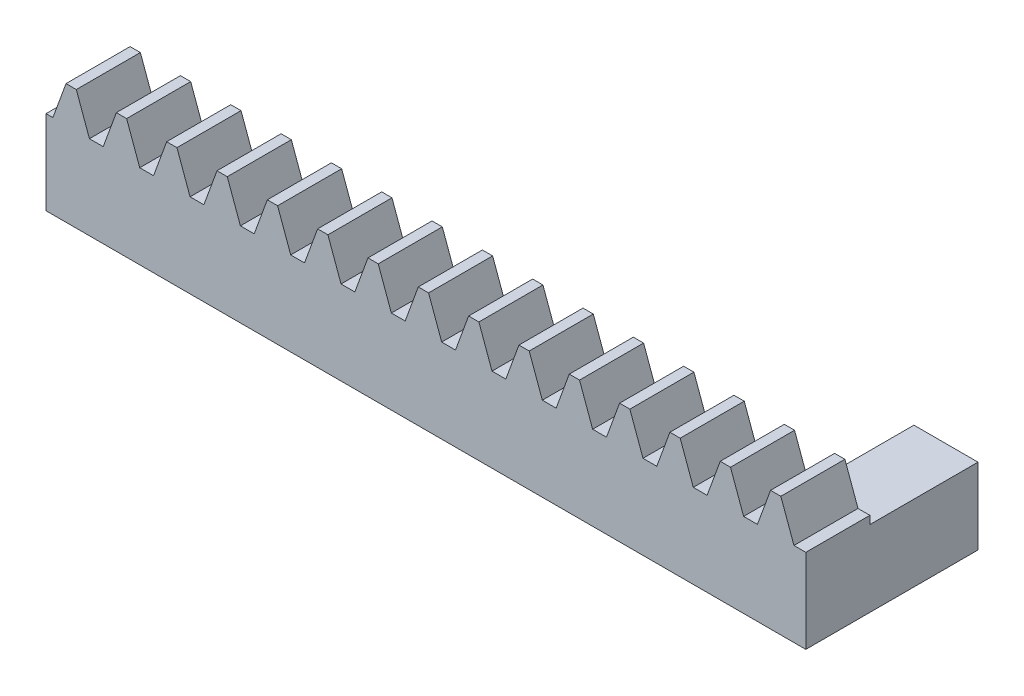
SolidWorks part; units mm, degrees
extrude "Blank" add sketch "BlankSke" against normal blind 8
sketch "BlankSke" plane through (0, 0, 0) normal (0, 0, 1) x (1, 0, 0)
  line L1 (0, 0) -> (120, 0)
  line L2 (0, 0) -> (0, 16)
  line L3 (0, 16) -> (120, 16)
  line L4 (120, 0) -> (120, 16)
  dimension "Length" = 120
  dimension "Blank_height" = 16
ref_plane "Plane1" through (0, 0, 0) normal (0, 0, 1) x (1, 0, 0)
ref_plane "Plane2" through (0, 0, 0) normal (0, 1, 0) x (1, 0, 0)
ref_plane "Plane3" through (0, 0, 0) normal (1, 0, 0) x (0, 0, -1)
sketch "HoldingSke" plane through (0, 0, 0) normal (0, 1, 0) x (1, 0, 0)
  line L0 (0, 0) -> (0.0696, 0.4951)
  line L1 (-15, 0) -> (100, 0) construction
  line L2 (0, 0) -> (-2.1039, 2.3779)
  line L3 (0, 0) -> (-11.863, 4.5341)
  line L4 (0, 0) -> (8.0624, 3.0949)
  line L5 (0, 0) -> (-23.7986, -8.8762)
  line L6 (0, 0) -> (-10.5278, -7.1032)
  line L9 (-71.009, 38.7566) -> (41.7541, 79.799)
  line L10 (-76.2, 4.3779) -> (-62.2, 4.3779)
  line L11 (0, 0) -> (-8, 0)
  line L12 (-76.2, 101.6) -> (-76.133, 101.6)
  line L13 (24.9733, 27.94) -> (52.9518, 28.4284)
  line L14 (24.9733, 27.94) -> (24.9743, 27.94)
  line L15 (24.9733, 27.94) -> (100.4006, 29.5858)
  circle A0 centre (0, 0) radius 19.05
  circle A1 centre (0, 0) radius 7
  circle A2 centre (0, 0) radius 12.7
  dimension "MPH" = 14
  dimension "Diameter" = 38.1
  dimension "Num_teeth" = 21
  dimension "Pitch" = 0.5
  dimension "Show_teeth" = 998
  dimension "Thickness" = 12.7
  dimension "Ap" = 20
  dimension "Pitch_height" = 14
  dimension "Width" = 8
  dimension "Backlash" = 0.067
  dimension "Addendum_fac" = 1
  dimension "Dedendum_fac" = 1.25
  dimension "Clearance_fac" = 0.25
  dimension "Dedendum_add" = 0.001
  dimension "Length" = 120
  dimension "Module" = 2
sketch "TooCutSkeIll" plane through (0, 0, 0) normal (0, 0, 1) x (1, 0, 0)
  line L0 (-2.4806, 15.9474) -> (-0.9819, 11.8296)
  line L1 (-0.5111, 11.5) -> (0.5111, 11.5)
  line L2 (0.9819, 11.8296) -> (2.4806, 15.9474)
  line L3 (120, 16) -> (0, 16) construction
  line L4 (0, 0) -> (0, 64.897) construction
  line L5 (-13.208, 14) -> (12.954, 14) construction
  line L6 (0, 0) -> (120, 0) construction
  line L7 (1.7718, 14) -> (1.7718, 48.7463) construction
  line L8 (-1.7718, 14) -> (-1.7718, 48.7463) construction
  line L9 (2.5558, 16) -> (2.5558, 16.0254)
  line L10 (-2.5558, 16) -> (-2.5558, 16.0254)
  line L11 (-2.5558, 16.0254) -> (2.5558, 16.0254)
  arc A0 (0.5111, 11.5) -> (0.9819, 11.8296) centre (0.5111, 12.001) ccw
  arc A1 (-0.9819, 11.8296) -> (-0.5111, 11.5) centre (-0.5111, 12.001) ccw
  arc A2 (2.5558, 16) -> (2.4806, 15.9474) centre (2.5558, 15.92) ccw
  arc A3 (-2.4806, 15.9474) -> (-2.5558, 16) centre (-2.5558, 15.92) ccw
  dimension "Pitch_height" = 14
  dimension "Addendum_plus" = 2.0254
  dimension "Pressure_angle" = 20
  dimension "Gap_width" = 3.5436
  dimension "Dedendum" = 2.5
extrude "ToothCutIll" [suppressed] cut sketch "TooCutSkeIll" against normal through all
sketch "TooCutSkeSim" plane through (0, 0, 0) normal (0, 0, 1) x (1, 0, 0)
  line L0 (0.8619, 11.5) -> (-0.8619, 11.5)
  line L1 (2.509, 16.0254) -> (0.8619, 11.5)
  line L2 (0, 17.4625) -> (0, 53.467) construction
  line L3 (2.509, 16.0254) -> (-2.509, 16.0254)
  line L6 (-2.509, 16.0254) -> (-0.8619, 11.5)
  line L9 (-1.7718, 14) -> (1.7718, 14) construction
  line L10 (0, 0) -> (120, 0) construction
  line L11 (1.7718, 14) -> (1.7718, 53.467) construction
  line L12 (-1.7718, 14) -> (-1.7718, 53.467) construction
  dimension "Pitch_height" = 14
  dimension "Addendum_plus" = 2.0254
  dimension "Pressure_angle" = 20
  dimension "Gap_width" = 3.5436
  dimension "Dedendum" = 2.5
extrude "ToothCutSim" cut sketch "TooCutSkeSim" against normal through all
pattern_linear "TeethCuts" count 20 spacing 6.2832 along (1, 0, 0) of "ToothCutIll", "ToothCutSim"
sketch "Sketch1" plane through (120, 0, 0) normal (1, 0, 0) x (0, 0, -1)
  line L0 (0, 1) -> (8, 1)
  line L1 (0, 0) -> (0, 11.5) construction
  line L2 (8, 0) -> (8, 11.5) construction
  line L3 (8, 1) -> (8, 0)
  line L4 (8, 0) -> (0, 0)
  line L5 (0, 0) -> (0, 1)
  dimension "D1" = 1
extrude "Cut-Extrude1" cut sketch "Sketch1" against normal through all
sketch "Sketch2" plane through (120, 0, 0) normal (1, 0, 0) x (0, 0, -1)
  line L0 (8, 1) -> (21.5, 1)
  line L6 (21.5, 10.5) -> (8, 10.5)
  line L7 (8, 1) -> (8, 11.5) construction
  line L8 (8, 10.5) -> (8, 1)
  line L14 (21.5, 10.5) -> (21.5, 1)
  dimension "D1" = 9.5
  dimension "D6" = 13.5
extrude "Boss-Extrude2" add sketch "Sketch2" against normal blind 8
sketch "Sketch3" plane through (0, 0, 0) normal (0, 0, 1) x (1, 0, 0)
  line L0 (0, 1) -> (0, 11.5)
  line L1 (0, 11.5) -> (0, 1) construction
  line L2 (0.8619, 11.5) -> (2.4997, 16)
  line L3 (2.4997, 16) -> (3.7834, 16)
  line L4 (3.7834, 16) -> (5.4213, 11.5)
  line L6 (5.4213, 11.5) -> (7.1451, 11.5) construction
  line L8 (0, 1) -> (120, 1) construction
  line L9 (6.1613, 1) -> (0, 1)
  line L10 (5.4213, 11.5) -> (7.1451, 11.5)
  line L11 (7.1451, 11.5) -> (8.7829, 16)
  line L12 (8.7829, 16) -> (10.0666, 16)
  line L13 (10.0666, 16) -> (11.7045, 11.5)
  line L14 (11.7045, 11.5) -> (13.4282, 11.5)
  line L15 (13.4282, 11.5) -> (15.0661, 16)
  line L16 (15.0661, 16) -> (15.708, 16)
  line L17 (16.3498, 16) -> (15.0661, 16) construction
  line L19 (0, 1) -> (112, 1) construction
  line L20 (15.708, 1) -> (6.1613, 1)
  line L21 (15.708, 16) -> (16.3498, 16)
  line L22 (16.3498, 16) -> (17.9877, 11.5)
  line L23 (17.9877, 11.5) -> (19.7114, 11.5)
  line L25 (19.7114, 11.5) -> (21.3493, 16)
  line L26 (17.9877, 1) -> (15.708, 1)
  line L27 (21.3493, 16) -> (22.633, 16)
  line L28 (22.633, 16) -> (24.2709, 11.5)
  line L29 (24.2709, 11.5) -> (25.1327, 11.5)
  line L40 (25.1327, 1) -> (17.9877, 1)
  line L49 (25.1327, 11.5) -> (25.1327, 1)
  arc A0 (0, 11.5) -> (0.8619, 11.5) centre (0.4309, 11.5) cw
extrude "Cut-Extrude2" cut sketch "Sketch3" against normal through all
equation "' \"Module@HoldingSke\" = 6.35"
equation "' \"Num_teeth@HoldingSke\" = 12"
equation "' \"Ap@HoldingSke\" =  20"
equation "' \"Ap@HoldingSke\" = 20"
equation "' \"Width@HoldingSke\" = 0.25 * 25.4"
equation "' \"Show_teeth@HoldingSke\" = 500"
equation "' \"Backlash@HoldingSke\" = 0.009 * 25.4"
equation "' \"Addendum_fac@HoldingSke\" = 1.0"
equation "' \"Dedendum_fac@HoldingSke\" = 1.25"
equation "' \"Dedendum_add@HoldingSke\" = 0.00005 * 25.4"
equation "' \"Clearance_fac@HoldingSke\" = 0.25"
equation "' \"Pitch_height@HoldingSke\" = 1 * 25.4"
equation "' \"Length@HoldingSke\" = 4.71 * 25.4"
equation "\"Pitch@HoldingSke\" = 1 / \"Module@HoldingSke\""
equation "\"MPH@HoldingSke\" = \"Dedendum_fac@HoldingSke\" / \"Pitch@HoldingSke\" + 2 * \"Dedendum_add@HoldingSke\" + 0.002 * 25.4"
equation "\"MPH@HoldingSke\" = ((sgn( \"MPH@HoldingSke\" - \"Pitch_height@HoldingSke\")+1)*( \"MPH@HoldingSke\" - \"Pitch_height@HoldingSke\"))/2 + \"Pitch_height@HoldingSke\""
equation "\"Blank_height@BlankSke\" = \"Pitch_height@HoldingSke\" + \"Addendum_fac@HoldingSke\"  / \"Pitch@HoldingSke\" "
equation "\"Length@BlankSke\" =  \"Length@HoldingSke\""
equation "\"Face_width@Blank\" = \"Width@HoldingSke\""
equation "\"Pressure_angle@TooCutSkeIll\" = \"Ap@HoldingSke\""
equation "\"Addendum_plus@TooCutSkeIll\" =  \"Addendum_fac@HoldingSke\"  / \"Pitch@HoldingSke\" + 0.001 *25.4"
equation "\"Dedendum@TooCutSkeIll\" = \"Dedendum_fac@HoldingSke\"  / \"Pitch@HoldingSke\""
equation "\"Pitch_height@TooCutSkeIll\" =  \"MPH@HoldingSke\""
equation "\"Gap_width@TooCutSkeIll\" = 3.14159265 / 2 / \"Pitch@HoldingSke\" + 6 * \"Backlash@HoldingSke\""
equation "\"Pressure_angle@TooCutSkeSim\" = \"Ap@HoldingSke\""
equation "\"Addendum_plus@TooCutSkeSim\" =  \"Addendum_fac@HoldingSke\"  / \"Pitch@HoldingSke\" + 0.001 * 25.4"
equation "\"Dedendum@TooCutSkeSim\" = \"Dedendum_fac@HoldingSke\"  / \"Pitch@HoldingSke\""
equation "\"Pitch_height@TooCutSkeSim\" =  \"MPH@HoldingSke\""
equation "\"Gap_width@TooCutSkeSim\" = 3.14159265 / 2 / \"Pitch@HoldingSke\" + 6 * \"Backlash@HoldingSke\""
equation "\"Root_fillet@TooCutSkeIll\" = \"Clearance_fac@HoldingSke\" / \"Pitch@HoldingSke\" + \"Dedendum_add@HoldingSke\""
equation "\"Break_rad@TooCutSkeIll\" = 0.02 / \"Pitch@HoldingSke\" * 2"
equation "\"Linear_pitch@TeethCuts\" = 3.14159265 / \"Pitch@HoldingSke\""
equation "\"Num_teeth@HoldingSke\" = int( ( \"Length@HoldingSke\" + 0 ) / (3.14159265 / \"Pitch@HoldingSke\")) + 0.9999  + 1"
equation " \"Num_teeth@TeethCuts\" = int( \"Show_teeth@HoldingSke\" ) + 1"
equation " \"Num_teeth@TeethCuts\" = ((sgn( \"Num_teeth@TeethCuts\" - \"Num_teeth@HoldingSke\" )-1)*( \"Num_teeth@TeethCuts\" - \"Num_teeth@HoldingSke\" ))/-2+ \"Num_teeth@HoldingSke\""
equation " \"Num_teeth@TeethCuts\" = ((sgn( \"Num_teeth@TeethCuts\" - 2.0)+1)*( \"Num_teeth@TeethCuts\" - 2.0))/2 +2.0"
